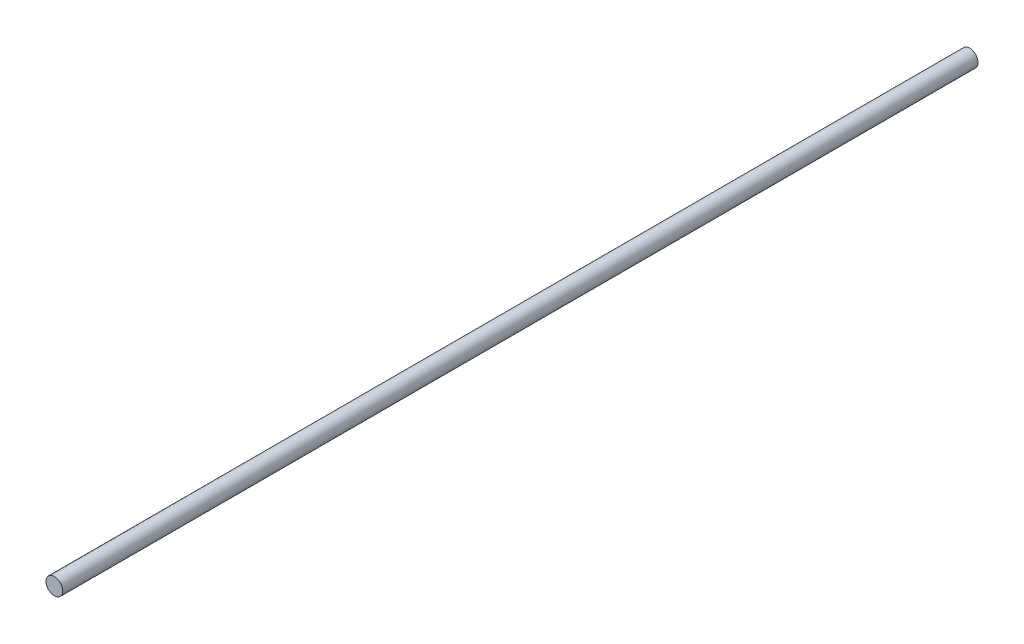
SolidWorks part; units mm, degrees
ref_plane "正面" through (0, 0, 0) normal (0, 0, 1) x (1, 0, 0)
ref_plane "平面" through (0, 0, 0) normal (0, 1, 0) x (1, 0, 0)
ref_plane "右側面" through (0, 0, 0) normal (1, 0, 0) x (0, 0, -1)
sketch "ｽｹｯﾁ1" plane through (0, 0, 0) normal (0, 0, 1) x (1, 0, 0)
  circle A0 centre (0, 0) radius 2.75
  dimension "D1" = 5.5
extrude "ﾎﾞｽ - 押し出し1" add sketch "ｽｹｯﾁ1" along normal blind 300
